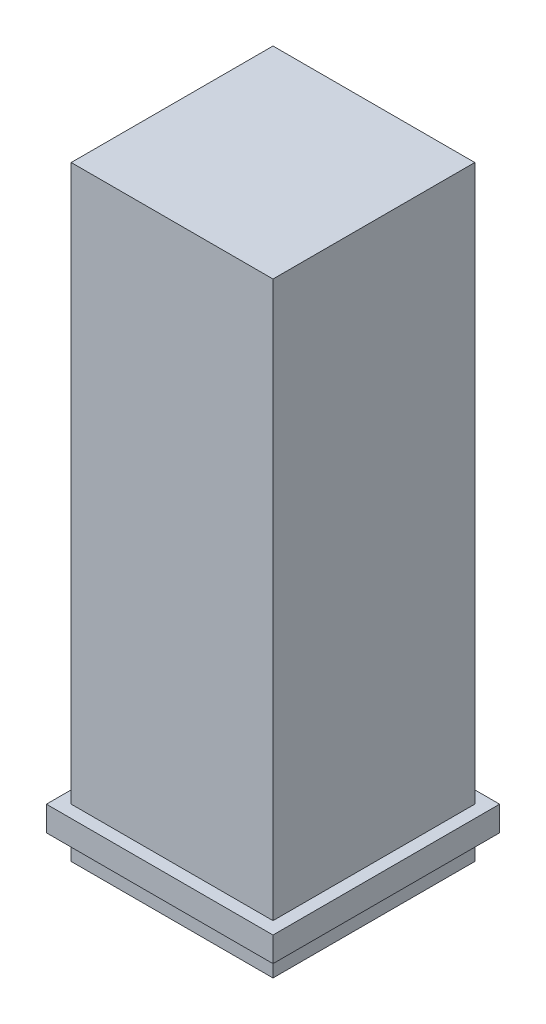
SolidWorks part; units mm, degrees
ref_plane "Front Plane" through (0, 0, 0) normal (0, 0, 1) x (1, 0, 0)
ref_plane "Top Plane" through (0, 0, 0) normal (0, 1, 0) x (1, 0, 0)
ref_plane "Right Plane" through (0, 0, 0) normal (1, 0, 0) x (0, 0, -1)
sketch "Sketch2" plane through (0, 0, 0) normal (0, 1, 0) x (1, 0, 0)
  line L1 (0, 0) -> (812.8, 0)
  line L2 (0, 0) -> (0, 812.8)
  line L3 (0, 812.8) -> (812.8, 812.8)
  line L4 (812.8, 0) -> (812.8, 812.8)
  dimension "D1" = 812.8
  dimension "D2" = 812.8
extrude "Boss-Extrude1" add sketch "Sketch2" along normal blind 2438.4
ref_plane "Plane1" through (0, 100, 0) normal (0, 1, 0) x (1, 0, 0)
sketch "Sketch3" plane through (0, 100, 0) normal (0, 1, 0) x (1, 0, 0)
  line L1 (-50, -50) -> (862.8, -50)
  line L2 (-50, -50) -> (-50, 862.8)
  line L3 (-50, 862.8) -> (862.8, 862.8)
  line L4 (862.8, -50) -> (862.8, 862.8)
  line L6 (0, 0) -> (812.8, 0)
  line L7 (0, 0) -> (0, 812.8)
  line L8 (0, 812.8) -> (812.8, 812.8)
  line L9 (812.8, 0) -> (812.8, 812.8)
  dimension "D1" = 812.8
  dimension "D2" = 812.8
  dimension "D3" = 50
  dimension "D4" = 50
  dimension "D5" = 50
  dimension "D6" = 50
extrude "Boss-Extrude2" add sketch "Sketch3" along normal blind 100
